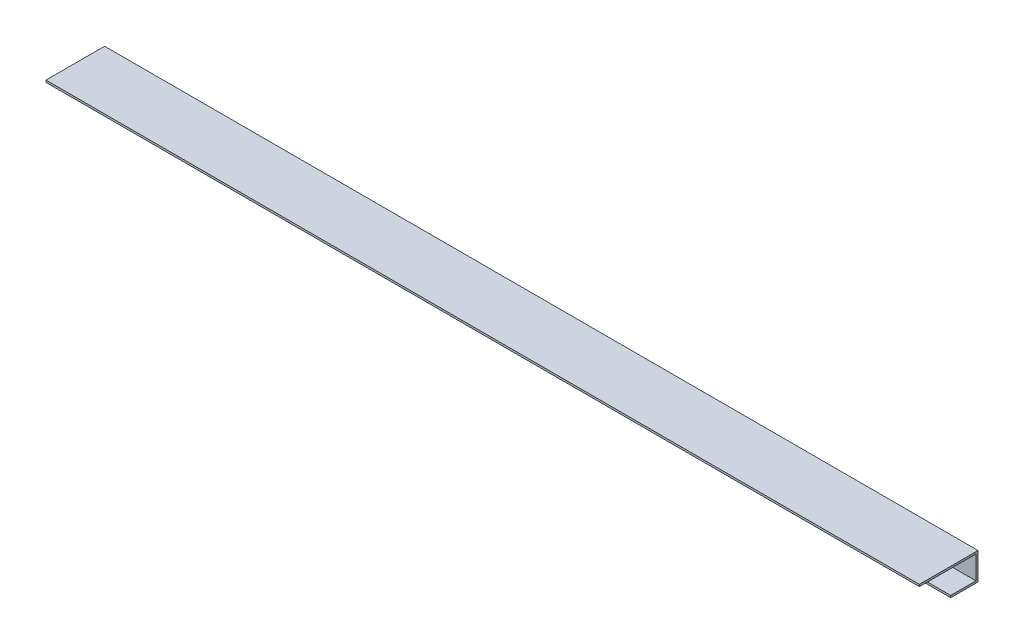
SolidWorks part; units mm, degrees
ref_plane "Front Plane" through (0, 0, 0) normal (0, 0, 1) x (1, 0, 0)
ref_plane "Top Plane" through (0, 0, 0) normal (0, 1, 0) x (1, 0, 0)
ref_plane "Right Plane" through (0, 0, 0) normal (1, 0, 0) x (0, 0, -1)
sketch "Sketch1" plane through (0, 0, 0) normal (1, 0, 0) x (0, 0, -1)
  line L0 (0, 0) -> (58, 0)
  line L1 (58, 0) -> (58, -27)
  line L2 (58, -27) -> (31, -27)
  line L3 (0, -2) -> (56, -2)
  line L4 (56, -2) -> (56, -25)
  line L5 (56, -25) -> (31, -25)
  line L6 (0, 0) -> (0, -2)
  line L7 (31, -25) -> (31, -27)
  dimension "D1" = 2
  dimension "D2" = 58
  dimension "D3" = 27
  dimension "D4" = 27
extrude "Boss-Extrude1" add sketch "Sketch1" along normal blind 864
equation "\"door_base_short7_R1_L_open_Single_width\"=864"
equation "\"D1@Boss-Extrude1\"= \"door_base_short7_L1_L_open_Single_width\""
equation "\"CarBeamWidth\"=700.0"
equation "\"WheelWidth\"=650.0"
equation "\"Wheel_FrontBoxDistance\"=1390.0"
equation "\"MetalSheet_3mm_length\"=5030.0"
equation "\"MetalSheet_3mm_width\"=1923.0"
equation "\"MetalSheet_3mm_FloorCut_L_length\"=1764.0"
equation "\"MetalSheet_3mm_FloorCut_L_disdance\"=1665.0"
equation "\"MetalSheet_3mm_FloorCut_R_length\"=1764.0"
equation "\"MetalSheet_3mm_FloorCut_R_disdance\"=1665.0"
equation "\"indoorHeight\"=1940.0"
equation "\"haveDoor_R\"=1"
equation "\"side_door_bottom_R_3mm_length\"=1934.0"
equation "\"1Bar_Side_RF_3mm_length\"=1493.0"
equation "\"1Bar_Side_RB_3mm_length\"=1493.0"
equation "\"DoorSeparator_RF_3mm_withHinge_toFrontDistance\"=1673.0"
equation "\"DoorSeparator_RF_3mm_withHinge_exist\"=1"
equation "\"DoorSeparator_RB_3mm_withHinge_toFrontDistance\"=3427.0"
equation "\"DoorSeparator_RB_3mm_withHinge_exist\"=1"
equation "\"Door_R1_L_open_Single_toFrontDistance\"=2547.5"
equation "\"Door_R1_L_open_Single_exist\"=1"
equation "\"door_base_long7_R1_L_open_Single_height\"=1890.0"
equation "\"door_base_short7_R1_L_open_Single_height\"=1890.0"
equation "\"Door_R1_R_open_Single_toFrontDistance\"=3422.0"
equation "\"Door_R1_R_open_Single_exist\"=1"
equation "\"door_base_long7_R1_R_open_Single_height\"=1890.0"
equation "\"door_base_short7_R1_R_open_Single_height\"=1890.0"
equation "\"door_base_short7_R1_R_open_Single_width\"=864"
equation "\"x\"=66.0"
equation "\"da\"=62.0"
equation "\"SquareTube_length\"=1923.0"
equation "\"channelSteel_length\"=5030.0"
equation "\"SquareTube_inFront_AvgDistance\"=285.0"
equation "\"SquareTube_inFront_TotalCount\"=5"
equation "\"SquareTube_inFront1_cutDepth50_R\"=0.5"
equation "\"SquareTube_inFront1_cutDepth50_L\"=0.5"
equation "\"SquareTube_inFront2_cutDepth50_R\"=0.5"
equation "\"SquareTube_inFront2_cutDepth50_L\"=0.5"
equation "\"SquareTube_inFront3_cutDepth50_R\"=0.5"
equation "\"SquareTube_inFront3_cutDepth50_L\"=0.5"
equation "\"SquareTube_inFront4_cutDepth50_R\"=0.5"
equation "\"SquareTube_inFront4_cutDepth50_L\"=0.5"
equation "\"SquareTube_inFront5_cutDepth50_R\"=50"
equation "\"SquareTube_inFront5_cutDepth50_L\"=50"
equation "\"SquareTube_inFront6_cutDepth50_R\"=50"
equation "\"SquareTube_inFront6_cutDepth50_L\"=50"
equation "\"SquareTube_inFront7_cutDepth50_R\"=50"
equation "\"SquareTube_inFront7_cutDepth50_L\"=50"
equation "\"SquareTube_inFront8_cutDepth50_R\"=50"
equation "\"SquareTube_inFront8_cutDepth50_L\"=50"
equation "\"SquareTube_inFront9_cutDepth50_R\"=50"
equation "\"SquareTube_inFront9_cutDepth50_L\"=50"
equation "\"SquareTube_inFront10_cutDepth50_R\"=50"
equation "\"SquareTube_inFront10_cutDepth50_L\"=50"
equation "\"SquareTube_inFront11_cutDepth50_R\"=50"
equation "\"SquareTube_inFront11_cutDepth50_L\"=50"
equation "\"SquareTube_inFront12_cutDepth50_R\"=50"
equation "\"SquareTube_inFront12_cutDepth50_L\"=50"
equation "\"SquareTube_inFront13_cutDepth50_R\"=50"
equation "\"SquareTube_inFront13_cutDepth50_L\"=50"
equation "\"SquareTube_inFront14_cutDepth50_R\"=50"
equation "\"SquareTube_inFront14_cutDepth50_L\"=50"
equation "\"SquareTube_inBack_AvgDistance\"=333.125"
equation "\"SquareTube_inBack_TotalCount\"=9"
equation "\"SquareTube_inBack1_cutDepth50_R\"=50"
equation "\"SquareTube_inBack1_cutDepth50_L\"=50"
equation "\"SquareTube_inBack2_cutDepth50_R\"=50"
equation "\"SquareTube_inBack2_cutDepth50_L\"=50"
equation "\"SquareTube_inBack3_cutDepth50_R\"=50"
equation "\"SquareTube_inBack3_cutDepth50_L\"=50"
equation "\"SquareTube_inBack4_cutDepth50_R\"=50"
equation "\"SquareTube_inBack4_cutDepth50_L\"=50"
equation "\"SquareTube_inBack5_cutDepth50_R\"=50"
equation "\"SquareTube_inBack5_cutDepth50_L\"=50"
equation "\"SquareTube_inBack6_cutDepth50_R\"=0.5"
equation "\"SquareTube_inBack6_cutDepth50_L\"=0.5"
equation "\"SquareTube_inBack7_cutDepth50_R\"=0.5"
equation "\"SquareTube_inBack7_cutDepth50_L\"=0.5"
equation "\"SquareTube_inBack8_cutDepth50_R\"=0.5"
equation "\"SquareTube_inBack8_cutDepth50_L\"=0.5"
equation "\"boxLength\"=5100.0"
equation "\"boxWidth\"=1930.0"
equation "\"indoorHeight_para\"=25.0"
equation "\"rearLightHeight_para\"=265.0"
equation "\"doorColumnBar_A_FR_3mm_length_Cut\"=2310.0"
equation "\"A\"=0.0"
equation "\"side_door_bottom_R_3mm_toFrontDistance\"=1583.0"
equation "\"door_base_double_BL_height\"=1890.0"
equation "\"door_base_short7_BL_Single_height\"=1890.0"
equation "\"door_base_short7_BL_Single_width\"=864"
equation "\"door_base_long7_BR_Single_height\"=1890.0"
equation "\"door_base_short7_BR_Single_height\"=1890.0"
equation "\"door_base_short7_BR_Single_width\"=864"
equation "\"doorColumnBar_A_FL_3mm_length_Cut\"=2310.0"
equation "\"B\"=0.0"
equation "\"haveDoor_L\"=1"
equation "\"side_door_bottom_L_3mm_length\"=1934.0"
equation "\"side_door_bottom_L_3mm_toFrontDistance\"=1583.0"
equation "\"1Bar_Side_LF_3mm_length\"=1493.0"
equation "\"1Bar_Side_LB_3mm_length\"=1493.0"
equation "\"DoorSeparator_LF_3mm_withHinge_toFrontDistance\"=1673.0"
equation "\"DoorSeparator_LF_3mm_withHinge_exist\"=1"
equation "\"DoorSeparator_LB_3mm_withHinge_toFrontDistance\"=3427.0"
equation "\"DoorSeparator_LB_3mm_withHinge_exist\"=1"
equation "\"Door_L1_L_open_Single_toFrontDistance\"=3422.0"
equation "\"Door_L1_L_open_Single_exist\"=1"
equation "\"door_base_long7_L1_L_open_Single_height\"=1890.0"
equation "\"door_base_short7_L1_L_open_Single_height\"=1890.0"
equation "\"door_base_short7_L1_L_open_Single_width\"=864"
equation "\"Door_L1_R_open_Single_toFrontDistance\"=2547.5"
equation "\"Door_L1_R_open_Single_exist\"=1"
equation "\"door_base_long7_L1_R_open_Single_height\"=1890.0"
equation "\"door_base_short7_L1_R_open_Single_height\"=1890.0"
equation "\"door_base_short7_L1_R_open_Single_width\"=864"
